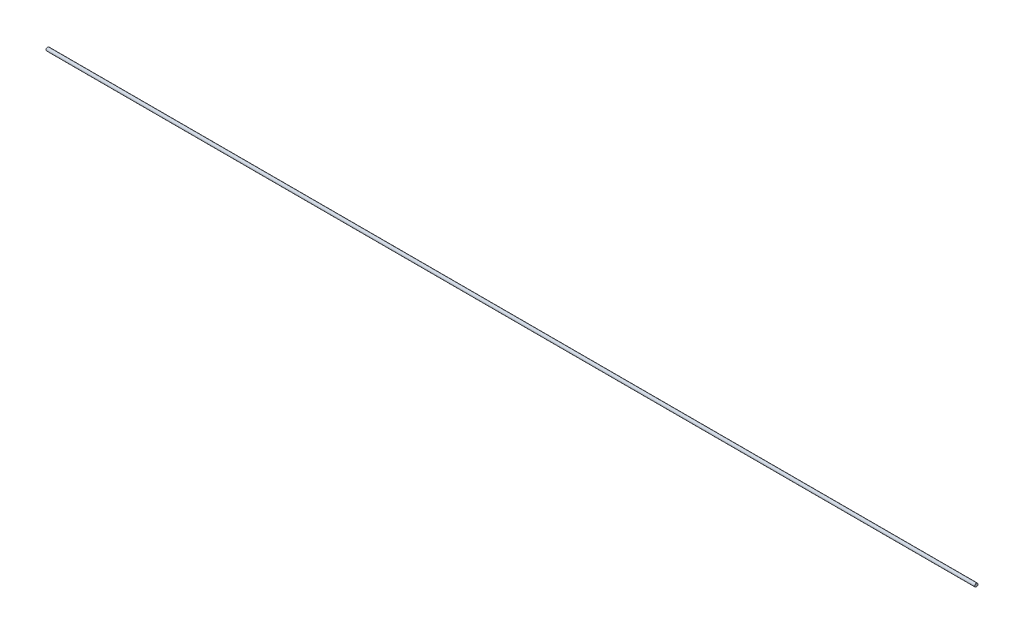
SolidWorks part; units mm, degrees
ref_plane "Front Plane" through (0, 0, 0) normal (0, 0, 1) x (1, 0, 0)
ref_plane "Top Plane" through (0, 0, 0) normal (0, 1, 0) x (1, 0, 0)
ref_plane "Right Plane" through (0, 0, 0) normal (1, 0, 0) x (0, 0, -1)
sketch "Sketch2" plane through (0, 0, 0) normal (1, 0, 0) x (0, 0, -1)
  circle A0 centre (0, 0) radius 1.0287
  dimension "D1" = 2.0574
extrude "Boss-Extrude1" add sketch "Sketch2" along normal blind 578.75
equation "\"Antenna_Diam\"= 0.081in'diameter of a coat hanger wire"
equation "\"D1@Sketch2\"=\"Antenna_Diam\""
equation "\"Quarter_Wavelength\"= 54.7cm'1/4 the wavelength of a 137MHz radiowave"
equation "\"D1@Boss-Extrude1\"=\"Quarter_Wavelength\"+\"Extra_Len_to_Connect\""
equation "\"Extra_Len_to_Connect\"= 1.25in'Guesstimate of extra length needed to mechanicaly assemble"
